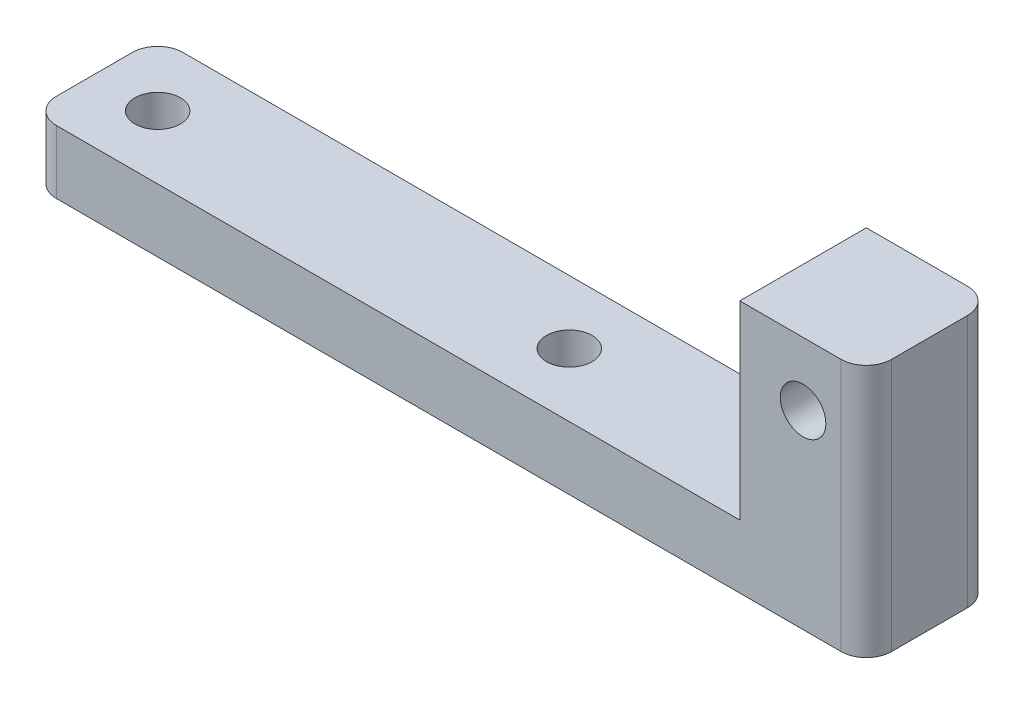
SolidWorks part; units mm, degrees
ref_plane "Front Plane" through (0, 0, 0) normal (0, 0, 1) x (1, 0, 0)
ref_plane "Top Plane" through (0, 0, 0) normal (0, 1, 0) x (1, 0, 0)
ref_plane "Right Plane" through (0, 0, 0) normal (1, 0, 0) x (0, 0, -1)
sketch "Sketch1" plane through (0, 0, 0) normal (0, 1, 0) x (1, 0, 0)
  line L1 (0, 0) -> (83.82, 0)
  line L2 (0, 0) -> (0, 12.7)
  line L3 (0, 12.7) -> (83.82, 12.7)
  line L4 (83.82, 0) -> (83.82, 12.7)
  circle A0 centre (6.35, 6.35) radius 2.286
  circle A1 centre (47.6592, 6.35) radius 2.286
  point P9 (0, 6.35)
  dimension "D3" = 4.572
  dimension "D1" = 6.35
  dimension "D2" = 12.7
  dimension "D4" = 41.3092
  dimension "D5" = 83.82
extrude "Boss-Extrude1" add sketch "Sketch1" along normal blind 25.4
sketch "Sketch2" plane through (0, 0, 0) normal (0, 0, 1) x (1, 0, 0)
  line L0 (83.82, 25.4) -> (83.82, 0) construction
  line L2 (0, 0) -> (83.82, 0) construction
  circle A0 centre (77.47, 19.05) radius 2.286
  dimension "D2" = 4.572
  dimension "D1" = 6.35
  dimension "D3" = 19.05
extrude "Cut-Extrude1" cut sketch "Sketch2" against normal blind 12.7
fillet "Fillet1" radius 2.54 4 edges at (83.82, 12.7, -12.7) (83.82, 12.7, 0) (0, 12.7, -12.7) (0, 12.7, 0)
sketch "Sketch3" plane through (0, 0, 0) normal (0, 0, 1) x (1, 0, 0)
  line L0 (2.54, 0) -> (81.28, 0) construction
  line L1 (0, 25.4) -> (71.12, 25.4)
  line L2 (0, 25.4) -> (0, 6.35)
  line L3 (0, 6.35) -> (71.12, 6.35)
  line L4 (71.12, 25.4) -> (71.12, 6.35)
  line L5 (83.82, 25.4) -> (83.82, 0) construction
  dimension "D1" = 6.35
  dimension "D2" = 12.7
extrude "Cut-Extrude2" cut sketch "Sketch3" against normal through all
